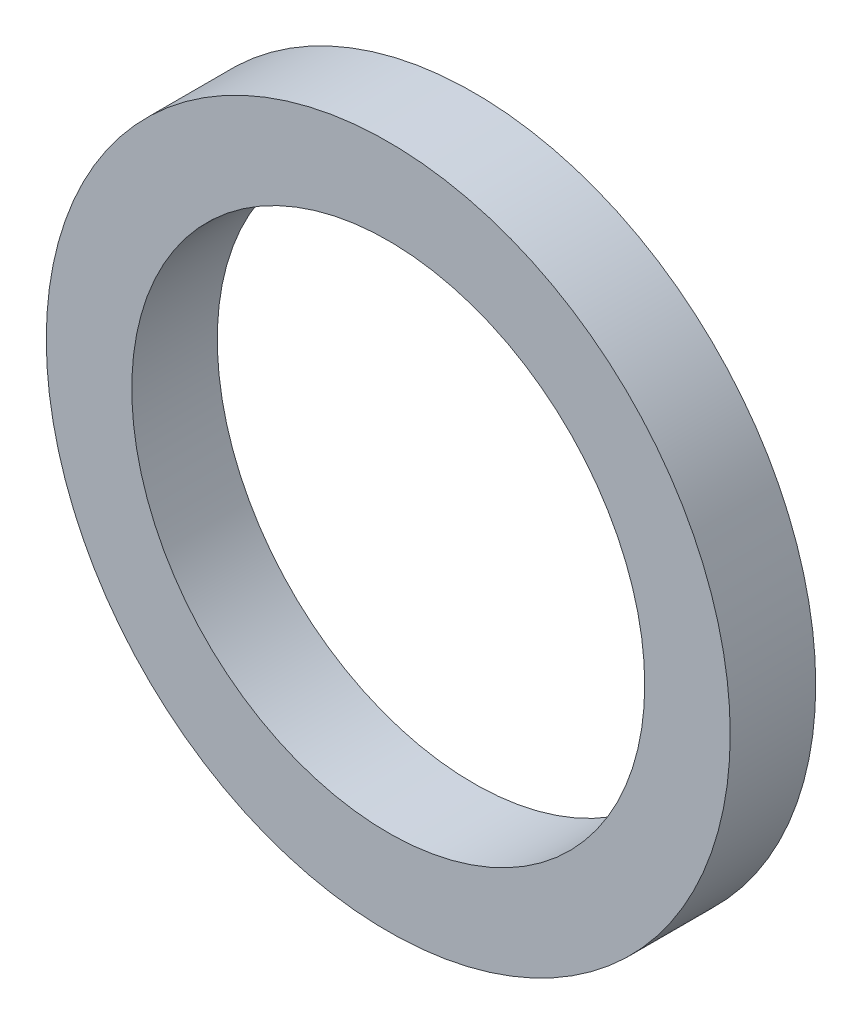
SolidWorks part; units mm, degrees
ref_plane "Front" through (0, 0, 0) normal (0, 0, 1) x (1, 0, 0)
ref_plane "Top" through (0, 0, 0) normal (0, 1, 0) x (1, 0, 0)
ref_plane "Right" through (0, 0, 0) normal (1, 0, 0) x (0, 0, -1)
sketch "Sketch1" plane through (0, 0, 0) normal (0, 0, 1) x (1, 0, 0)
  circle A0 centre (0, 0) radius 3
  circle A1 centre (0, 0) radius 4
extrude "Boss-Extrude1" add sketch "Sketch1" along normal blind 1
